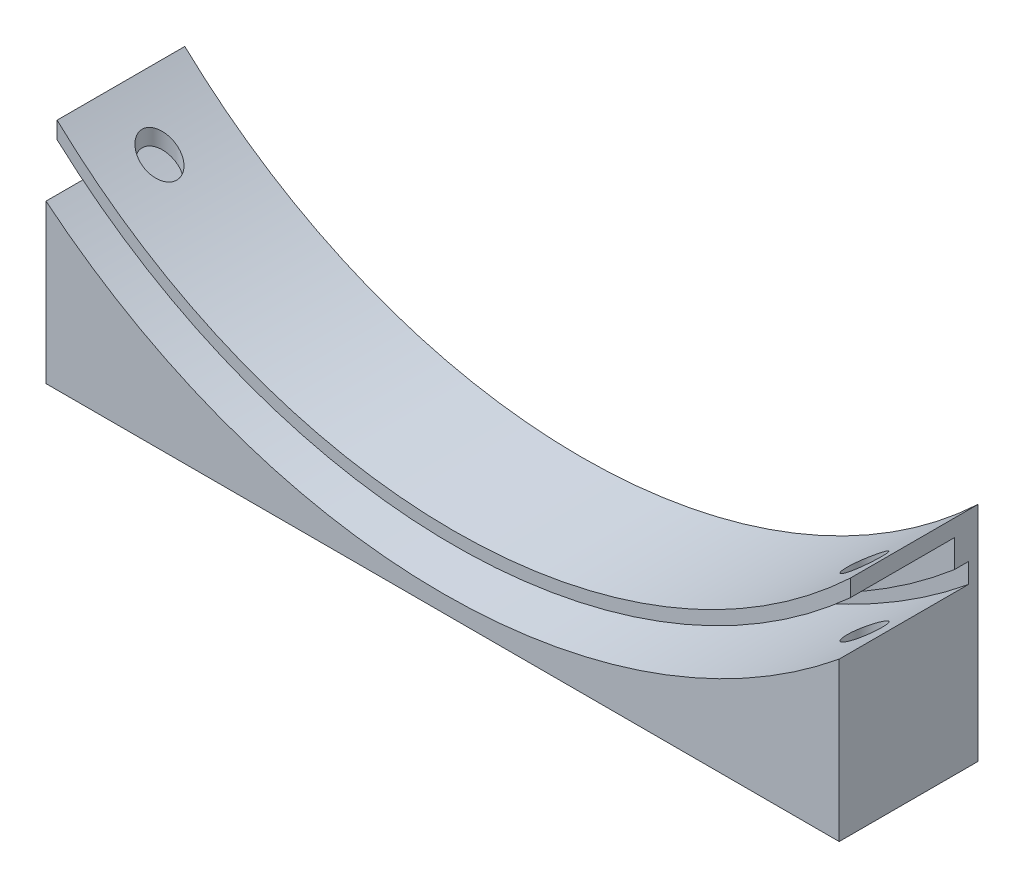
SolidWorks part; units mm, degrees
ref_plane "Front Plane" through (0, 0, 0) normal (0, 0, 1) x (1, 0, 0)
ref_plane "Top Plane" through (0, 0, 0) normal (0, 1, 0) x (1, 0, 0)
ref_plane "Right Plane" through (0, 0, 0) normal (1, 0, 0) x (0, 0, -1)
sketch "Sketch1" plane through (0, 0, 0) normal (0, 0, 1) x (1, 0, 0)
  line L1 (0, 0) -> (228.6, 0)
  line L2 (0, 0) -> (0, 70)
  line L3 (0, 70) -> (228.6, 70) construction
  line L4 (228.6, 0) -> (228.6, 70)
  arc A1 (0, 70) -> (228.6, 70) centre (114.3, 185.5065) ccw
  dimension "D1" = 228.6
  dimension "D3" = 162.5
  dimension "D2" = 70
extrude "Boss-Extrude1" add sketch "Sketch1" along normal blind 40
ref_point "Point1"
ref_plane "Plane4" through (114.3, 0, 0) normal (1, 0, 0) x (0, 0, -1)
sketch "Sketch2" plane through (114.3, 0, 0) normal (1, 0, 0) x (0, 0, -1)
  line L0 (-40, 70) -> (0, 70) construction
  line L1 (-33, 15.0065) -> (-7, 15.0065)
  line L2 (-33, 15.0065) -> (-33, 9.0065)
  line L3 (-33, 9.0065) -> (-7, 9.0065)
  line L4 (-7, 15.0065) -> (-7, 9.0065)
  line L6 (-40, 23.0065) -> (0, 23.0065) construction
  line L7 (-40, 23.0065) -> (0, 23.0065) construction
  point P6 (-20, 70)
  point P7 (-20, 15.0065)
  dimension "D1" = 6
  dimension "D2" = 26
  dimension "D3" = 8
ref_axis "Axis1" through (114.3, 185.5065, 40) along (0, 0, 1)
revolve "Cut-Revolve1" cut sketch "Sketch2" angle 360 about axis through (114.3, 185.5065, 40) along (0, 0, 1)
sketch "Sketch4" plane through (0, 0, 0) normal (0, -1, 0) x (1, 0, 0)
  line L0 (0, 20) -> (228.6, 20) construction
  line L1 (0, 40) -> (0, 0) construction
  line L2 (228.6, 40) -> (228.6, 0) construction
  line L3 (114.3, 80.0645) -> (114.3, -38.0645) construction
  line L4 (12.7, 20) -> (215.9, 20) construction
  circle A2 centre (12.7, 20) radius 2.5
  circle A3 centre (215.9, 20) radius 2.5
  point P9 (114.3, 20)
  point P13 (114.3, 20)
  dimension "D1" = 203.2
  dimension "D2" = 5
  dimension "D3" = 5
extrude "Cut-Extrude1" cut sketch "Sketch4" against normal through all both and the other way through all
ref_plane "Plane5" through (0, 70, 0) normal (0, -1, 0) x (-1, 0, 0)
sketch "Sketch7" plane through (0, 70, 0) normal (0, -1, 0) x (-1, 0, 0)
  circle A0 centre (-215.9, -20) radius 5
  circle A1 centre (-12.7, -20) radius 5
  dimension "D1" = 10
  dimension "D2" = 10
extrude "Cut-Extrude3" cut sketch "Sketch7" along normal offset from surface (56.8932 mm away) 8
sketch "Sketch8" plane through (114.3, 0, 0) normal (1, 0, 0) x (0, 0, -1)
  line L0 (-40, 0) -> (0, 0) construction
  line L1 (-40, 23.0065) -> (0, 23.0065) construction
  line L2 (-40, 0) -> (0, 0) construction
  line L3 (-40, 23.0065) -> (0, 23.0065) construction
  line L4 (-40, 23.0065) -> (-40, 0) construction
  line L5 (0, 23.0065) -> (0, 0) construction
  line L6 (-7, 15.0065) -> (-37, 15.0065)
  line L7 (-37, 15.0065) -> (-37, 19.0065)
  line L8 (-37, 19.0065) -> (0, 19.0065)
  line L12 (-40, 5.0065) -> (-3, 5.0065)
  line L14 (-33, 9.0065) -> (-7, 9.0065) construction
  line L15 (-33, 15.0065) -> (-7, 15.0065) construction
  line L16 (-7, 51.0158) -> (-7, 9.0065) construction
  line L17 (-7, 15.0065) -> (-7, 9.0065)
  line L18 (-7, 9.0065) -> (-3, 9.0065)
  line L19 (-3, 9.0065) -> (-3, 5.0065)
  line L20 (-33, 9.0065) -> (-33, 51.0158) construction
  line L21 (0, 19.0065) -> (0, -48.7775)
  line L22 (0, -48.7775) -> (-40, -48.7775)
  line L23 (-40, -48.7775) -> (-40, 5.0065)
  dimension "D1" = 4
  dimension "D2" = 4
  dimension "D3" = 4
  dimension "D4" = 4
sketch "Sketch9" plane through (114.3, 0, 0) normal (1, 0, 0) x (0, 0, -1)
  line L37 (0, 18.8065) -> (0, 23.0065)
  line L38 (0, 23.0065) -> (-40, 23.0065)
  line L39 (-40, 23.0065) -> (-40, 4.8065)
  line L44 (-40, 4.8065) -> (-2.8, 4.8065)
  line L45 (-2.8, 4.8065) -> (-2.8, 9.2065)
  line L46 (-2.8, 9.2065) -> (-6.8, 9.2065)
  line L47 (-6.8, 9.2065) -> (-6.8, 15.2065)
  line L48 (-6.8, 15.2065) -> (-36.8, 15.2065)
  line L49 (-36.8, 15.2065) -> (-36.8, 18.8065)
  line L50 (-36.8, 18.8065) -> (0, 18.8065)
  line L51 (-40, 4.8065) -> (-2.8, 4.8065)
  line L52 (-2.8, 4.8065) -> (-2.8, 9.2065)
  line L53 (-2.8, 9.2065) -> (-6.8, 9.2065)
  line L54 (-6.8, 9.2065) -> (-6.8, 15.2065)
  line L55 (-6.8, 15.2065) -> (-36.8, 15.2065)
  line L56 (-36.8, 15.2065) -> (-36.8, 18.8065)
  line L57 (-36.8, 18.8065) -> (0, 18.8065)
  dimension "D1" = 0.2
revolve "Cut-Revolve3" cut sketch "Sketch9" angle 360 about axis through (114.3, 185.5065, 40) along (0, 0, 1)
